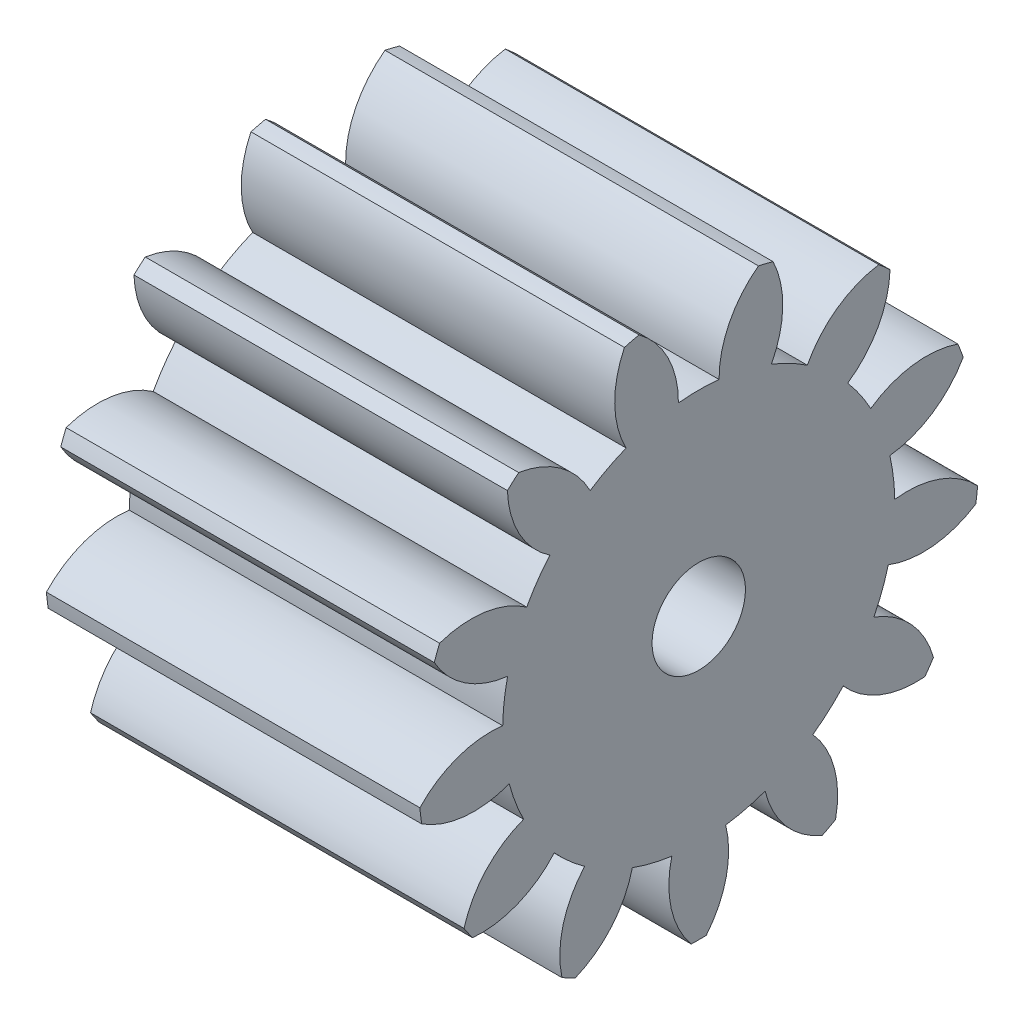
SolidWorks part; units mm, degrees
ref_plane "Plane1" through (0, 0, 0) normal (0, 0, 1) x (1, 0, 0)
ref_plane "Plane2" through (0, 0, 0) normal (0, 1, 0) x (1, 0, 0)
ref_plane "Plane3" through (0, 0, 0) normal (1, 0, 0) x (0, 0, -1)
sketch "HoldingSke" plane through (0, 0, 0) normal (0, 1, 0) x (1, 0, 0)
  line L0 (0, 0) -> (0.4872, -0.1125)
  line L1 (-15, 0) -> (100, 0) construction
  line L2 (0, 0) -> (-2.1039, 2.3779)
  line L3 (0, 0) -> (-11.863, 4.5341)
  line L4 (0, 0) -> (8.4147, 1.9427)
  line L5 (0, 0) -> (-46.8476, -17.4728)
  line L6 (0, 0) -> (-16.5793, -11.1861)
  line L7 (-2.1039, 2.3779) -> (8.6586, 51.2059)
  line L8 (-76.2, 54.61) -> (-75.3, 54.61)
  line L9 (-71.009, 38.7566) -> (-53.1078, 45.2721)
  line L10 (-76.2, 71.12) -> (104.1128, 71.12)
  line L11 (0, 0) -> (-20, 0)
  line L12 (-76.2, 101.6) -> (-76.133, 101.6)
  line L13 (24.9733, 27.94) -> (52.9518, 28.4284)
  line L14 (24.9733, 27.94) -> (24.9743, 27.94)
  line L15 (24.9733, 27.94) -> (100.4006, 29.5858)
  line L16 (-63.627, -2) -> (-12.827, -2)
  circle A0 centre (0, 0) radius 2.5
  circle A1 centre (0, 0) radius 10.499
  circle A2 centre (0, 0) radius 37.5
  circle A3 centre (0, 0) radius 2.5
  dimension "MHD" = 20.998
  dimension "Hub_dia" = 75
  dimension "Bore" = 5
  dimension "MBD" = 5
  dimension "Num_teeth" = 13
  dimension "Pitch" = 0.5
  dimension "Overall_len" = 50
  dimension "Show_teeth" = 13
  dimension "Thickness" = 20
  dimension "OAL" = 50.0001
  dimension "T_dim" = 0.9
  dimension "Ap" = 20
  dimension "H" = 19.05
  dimension "Pitch_radius" = 180.3128
  dimension "Width" = 20
  dimension "Backlash" = 0.067
  dimension "Addendum_fac" = 1
  dimension "Dedendum_fac" = 1.25
  dimension "Clearance_fac" = 0.25
  dimension "Dedendum_add" = 0.001
  dimension "Module" = 2
sketch "BasProSke" plane through (0, 0, 0) normal (0, 1, 0) x (1, 0, 0)
  line L0 (-10, 0) -> (60, 0) construction
  line L1 (0, 0) -> (0, 15)
  line L2 (0, 0) -> (20, 0)
  line L3 (20, 0) -> (20, 15)
  line L4 (20, 15) -> (0, 15)
  dimension "Thickness" = 20
  dimension "Diameter" = 30
revolve "Base-Revolve" add sketch "BasProSke" angle 360 about L0
sketch "TooCutSke" plane through (0, 0, 0) normal (1, 0, 0) x (0, 0, -1)
  line L1 (0, 0) -> (0, 107) construction
  line L2 (0, 0) -> (-1.6841, 12.8905) construction
  line L3 (0, 0) -> (-6.1834, 25.087) construction
  line L4 (-1.6841, 12.8905) -> (-3.0917, 12.5435) construction
  arc A0 (1.0882, 10.4424) -> (-1.0882, 10.4424) centre (0, 0) ccw
  arc A1 (3.2249, 14.6752) -> (-3.2249, 14.6752) centre (0, 0) ccw
  circle A2 centre (0, 0) radius 13 construction
  circle A3 centre (0, 0) radius 12.216 construction
  arc A4 (-1.0882, 10.4424) -> (-3.2249, 14.6752) centre (-6.2882, 10.4733) ccw
  arc A5 (3.2249, 14.6752) -> (1.0882, 10.4424) centre (6.2882, 10.4733) ccw
  dimension "Root_dia" = 20.998
  dimension "Overcut_dia" = 30.0508
  dimension "Pitch_dia" = 26
  dimension "Base_dia" = 24.432
  dimension "Flank_rad" = 5.2
  dimension "Half_ang" = 13.846
  dimension "Half_CT" = 1.4497
extrude "ToothCut" cut sketch "TooCutSke" along normal through all
fillet "Breaks" [suppressed] radius 0.04
fillet "RootFillets" [suppressed] radius 0.501
pattern_circular "TeethCuts" count 13 every 27.692 about axis through (-10, 0, 0) along (1, 0, 0) of "ToothCut", "RootFillets", "Breaks"
sketch "HubNeaOneSke" plane through (0, 0, 0) normal (-1, 0, 0) x (0, 0, 1)
  circle A0 centre (0, 0) radius 10.499
  dimension "Diameter" = 20.998
extrude "HubNearOne" [suppressed] add sketch "HubNeaOneSke" along normal blind 30.0001
sketch "HubNeaBotSke" plane through (0, 0, 0) normal (-1, 0, 0) x (0, 0, 1)
  circle A0 centre (0, 0) radius 10.499
  dimension "Diameter" = 20.998
extrude "HubNearBoth" [suppressed] add sketch "HubNeaBotSke" along normal blind 15
ref_plane "FarPln" through (20, 0, 0) normal (1, 0, 0) x (0, 0, -1)
sketch "HubFarSke" plane through (20, 0, 0) normal (1, 0, 0) x (0, 0, -1)
  circle A0 centre (0, 0) radius 10.499
  dimension "Diameter" = 20.998
extrude "HubFar" [suppressed] add sketch "HubFarSke" along normal blind 15
sketch "BorSke" plane through (0, 0, 0) normal (1, 0, 0) x (0, 0, -1)
  circle A0 centre (0, 0) radius 2.5
  dimension "Diameter" = 5
extrude "Bore" cut sketch "BorSke" along normal mid plane 100.0001
sketch "KeySke" plane through (0, 0, 0) normal (1, 0, 0) x (0, 0, -1)
  line L0 (-1, 0) -> (-1, 3.4)
  line L1 (-1, 3.4) -> (1, 3.4)
  line L2 (1, 3.4) -> (1, 0)
  line L3 (0, 0) -> (0, 34) construction
  line L4 (-1, 0) -> (1, 0)
  dimension "Offset" = 3.4
extrude "Keyway" [suppressed] cut sketch "KeySke" along normal mid plane 100.0001
pattern_circular "Keyway2" [suppressed] count 2 every 90 about axis through (-10, 0, 0) along (1, 0, 0)
equation "' \"Module@HoldingSke\" = 6.35"
equation "' \"Num_teeth@HoldingSke\" = 12"
equation "' \"Ap@HoldingSke\" =  20"
equation "' \"Ap@HoldingSke\" = 20"
equation "' \"Width@HoldingSke\" = 0.5 * 25.4"
equation "' \"Hub_dia@HoldingSke\"= 1 * 25.4"
equation "' \"Hub_dia@HoldingSke\" = 1 * 25.4"
equation "' \"Overall_len@HoldingSke\" = 1.0 * 25.4"
equation "' \"Bore@HoldingSke\" = 0.75 * 25.4"
equation "' \"T_dim@HoldingSke\" = 0.1 * 25.4"
equation "' \"Width@KeySke\" = 0.25 * 25.4"
equation "' \"Show_teeth@HoldingSke\" = 13"
equation "' \"Backlash@HoldingSke\" = 0.009 * 25.4"
equation "' \"Addendum_fac@HoldingSke\" = 1.0"
equation "' \"Dedendum_fac@HoldingSke\" = 1.25"
equation "' \"Dedendum_add@HoldingSke\" = 0.00005 * 25.4"
equation "' \"Clearance_fac@HoldingSke\" = 0.25"
equation "\"Pitch@HoldingSke\" = 1 / \"Module@HoldingSke\""
equation "\"Overcut_dia@TooCutSke\" = (\"Num_teeth@HoldingSke\" + 2 * \"Addendum_fac@HoldingSke\") / \"Pitch@HoldingSke\" + 0.002 * 25.4"
equation "\"Pitch_dia@TooCutSke\" = \"Num_teeth@HoldingSke\" / \"Pitch@HoldingSke\""
equation "\"Base_dia@TooCutSke\" = \"Num_teeth@HoldingSke\" / \"Pitch@HoldingSke\" * cos((\"Ap@HoldingSke\"  * 3.14159265 / 180))"
equation "\"Root_dia@TooCutSke\" = (\"Num_teeth@HoldingSke\" + 2) / \"Pitch@HoldingSke\" - 2 * (\"Addendum_fac@HoldingSke\" + \"Dedendum_fac@HoldingSke\") / \"Pitch@HoldingSke\" - \"Dedendum_add@HoldingSke\" * 2"
equation "\"Half_ang@TooCutSke\" = 180 / \"Num_teeth@HoldingSke\""
equation "\"Half_CT@TooCutSke\" = \"Num_teeth@HoldingSke\" / \"Pitch@HoldingSke\" * sin((3.14159265 / 2 / \"Num_teeth@HoldingSke\")) / 2 - 7 * \"Backlash@HoldingSke\" / 4"
equation "\"Flank_rad@TooCutSke\" = \"Num_teeth@HoldingSke\" / \"Pitch@HoldingSke\" / 5"
equation "\"Radius@RootFillets\" = \"Clearance_fac@HoldingSke\" / \"Pitch@HoldingSke\" + \"Dedendum_add@HoldingSke\""
equation "\"Break_rad@Breaks\" = 0.02 / \"Pitch@HoldingSke\""
equation "\"Thickness@HoldingSke\" = \"Width@HoldingSke\""
equation "\"OAL@HoldingSke\" = \"Thickness@HoldingSke\""
equation "\"MHD@HoldingSke\" = (\"Num_teeth@HoldingSke\" + 2) / \"Pitch@HoldingSke\" - 2 * (\"Addendum_fac@HoldingSke\" + \"Dedendum_fac@HoldingSke\")  / \"Pitch@HoldingSke\" - \"Dedendum_add@HoldingSke\" * 2"
equation "\"MBD@HoldingSke\" = (\"Num_teeth@HoldingSke\" + 2) / \"Pitch@HoldingSke\" - 2 * (\"Addendum_fac@HoldingSke\" + \"Dedendum_fac@HoldingSke\")  / \"Pitch@HoldingSke\" - \"Dedendum_add@HoldingSke\" * 2 - 0.002 * 25.4"
equation "\"MHD@HoldingSke\" = ((sgn( \"MHD@HoldingSke\" - \"Hub_dia@HoldingSke\" )-1)*( \"MHD@HoldingSke\" - \"Hub_dia@HoldingSke\" ))/-2+ \"Hub_dia@HoldingSke\""
equation "\"MBD@HoldingSke\" = ((sgn( \"MBD@HoldingSke\" - \"Bore@HoldingSke\" )-1)*( \"MBD@HoldingSke\" - \"Bore@HoldingSke\" ))/-2+ \"Bore@HoldingSke\""
equation "\"OAL@HoldingSke\" = ((sgn( \"OAL@HoldingSke\" - \"Overall_len@HoldingSke\" )+1)*( \"OAL@HoldingSke\" - \"Overall_len@HoldingSke\" ))/2 + \"Overall_len@HoldingSke\" + 0.000002 * 25.4"
equation "\"Num_teeth@TeethCuts\" = int( \"Show_teeth@HoldingSke\" ) + 1"
equation "\"Num_teeth@TeethCuts\" = ((sgn( \"Num_teeth@TeethCuts\" - \"Num_teeth@HoldingSke\" )-1)*( \"Num_teeth@TeethCuts\" - \"Num_teeth@HoldingSke\" ))/-2+ \"Num_teeth@HoldingSke\""
equation "\"Num_teeth@TeethCuts\" = ((sgn( \"Num_teeth@TeethCuts\" - 2.0)+1)*( \"Num_teeth@TeethCuts\" - 2.0))/2 +2.0"
equation "\"Angle@TeethCuts\" = 360.0 / \"Num_teeth@HoldingSke\""
equation "\"Diameter@BasProSke\" = (\"Num_teeth@HoldingSke\" + 2 * \"Addendum_fac@HoldingSke\") / \"Pitch@HoldingSke\""
equation "\"Thickness@BasProSke\"  = \"Thickness@HoldingSke\""
equation "' \"Fillet_rad@BasProSke\" =  \"Thickness@HoldingSke\" * 0.05"
equation "' \"Fillet_rad@BasProSke\" = \"Thickness@HoldingSke\" * 0.05"
equation "\"MHD@HoldingSke\" = ((sgn( \"MHD@HoldingSke\" - \"Root_dia@TooCutSke\" )-1)*( \"MHD@HoldingSke\" - \"Root_dia@TooCutSke\" ))/-2+ \"Root_dia@TooCutSke\""
equation "\"Diameter@HubNeaOneSke\" = \"MHD@HoldingSke\""
equation "\"Length@HubNearOne\" = \"OAL@HoldingSke\" - \"Thickness@BasProSke\""
equation "\"Diameter@HubNeaBotSke\" = \"MHD@HoldingSke\""
equation "\"Length@HubNearBoth\" = ( \"OAL@HoldingSke\" - \"Thickness@BasProSke\" ) / 2.0"
equation "\"Thickness@FarPln\" = \"Thickness@BasProSke\""
equation "\"Diameter@HubFarSke\" = \"MHD@HoldingSke\""
equation "\"Length@HubFar\" = ( \"OAL@HoldingSke\" - \"Thickness@BasProSke\" ) / 2.0"
equation "\"Diameter@BorSke\" = \"MBD@HoldingSke\""
equation "\"D1@Bore\" = \"OAL@HoldingSke\" * 2.0"
equation "\"D1@Keyway\" = \"OAL@HoldingSke\" * 2.0"
equation "\"Offset@KeySke\" = \"T_dim@HoldingSke\" + \"MBD@HoldingSke\" / 2.0"
